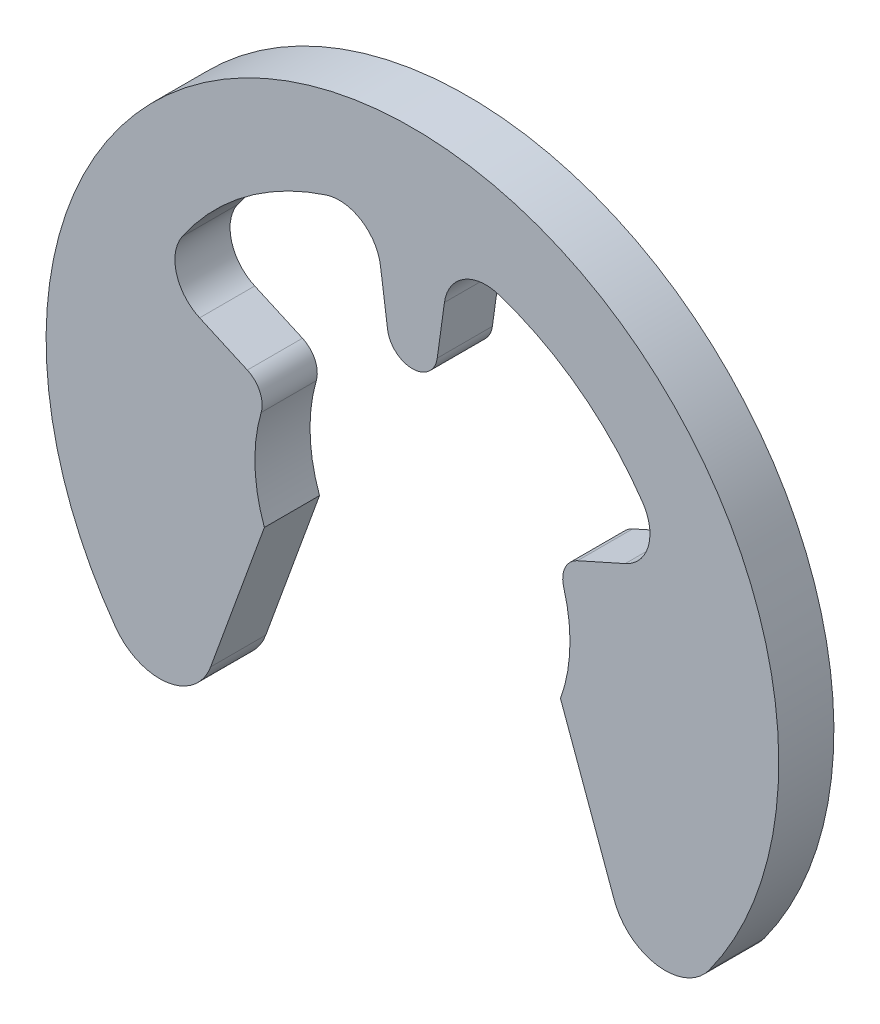
SolidWorks part; units mm, degrees
material "1.4122 (X39CrMo17-1)"
ref_plane "Front Plane" through (0, 0, 0) normal (0, 0, 1) x (1, 0, 0)
ref_plane "Top Plane" through (0, 0, 0) normal (0, 1, 0) x (1, 0, 0)
ref_plane "Right Plane" through (0, 0, 0) normal (1, 0, 0) x (0, 0, -1)
sketch "Sketch1" plane through (0, 0, 0) normal (0, 0, 1) x (1, 0, 0)
  line L0 (-2.5614, -2.5579) -> (-1.8794, -0.684)
  line L1 (-2.0957, 0.9381) -> (-2.7016, 1.2093)
  line L2 (-0.4061, 2.9319) -> (-0.315, 2.2744)
  line L3 (0.315, 2.2744) -> (0.4061, 2.9319)
  line L4 (2.7016, 1.2093) -> (2.0957, 0.9381)
  line L5 (1.8794, -0.684) -> (2.5614, -2.5579)
  arc A0 (-1.8794, -0.684) -> (-1.9203, 0.559) centre (0, 0) cw
  arc A1 (-1.9203, 0.559) -> (-2.0957, 0.9381) centre (-2.2256, 0.6479) ccw
  arc A2 (-2.7016, 1.2093) -> (-2.9231, 1.9915) centre (-2.4851, 1.6931) cw
  arc A3 (-2.9231, 1.9915) -> (-1.0952, 3.3632) centre (0, 0) cw
  arc A4 (-1.0952, 3.3632) -> (-0.4061, 2.9319) centre (-0.9311, 2.8592) cw
  arc A5 (-0.315, 2.2744) -> (0.315, 2.2744) centre (0, 2.318) ccw
  arc A6 (0.4061, 2.9319) -> (1.0952, 3.3632) centre (0.9311, 2.8592) cw
  arc A7 (1.0952, 3.3632) -> (2.9231, 1.9915) centre (0, 0) cw
  arc A8 (2.9231, 1.9915) -> (2.7016, 1.2093) centre (2.4851, 1.6931) cw
  arc A9 (2.0957, 0.9381) -> (1.9203, 0.559) centre (2.2256, 0.6479) ccw
  arc A10 (1.9203, 0.559) -> (1.8794, -0.684) centre (0, 0) cw
  arc A11 (2.5614, -2.5579) -> (3.767, -2.7262) centre (3.2089, -2.3222) ccw
  arc A12 (3.767, -2.7262) -> (-3.767, -2.7262) centre (0, 0) ccw
  arc A13 (-3.767, -2.7262) -> (-2.5614, -2.5579) centre (-3.2089, -2.3222) ccw
extrude "Boss-Extrude1" add sketch "Sketch1" against normal blind 0.7
